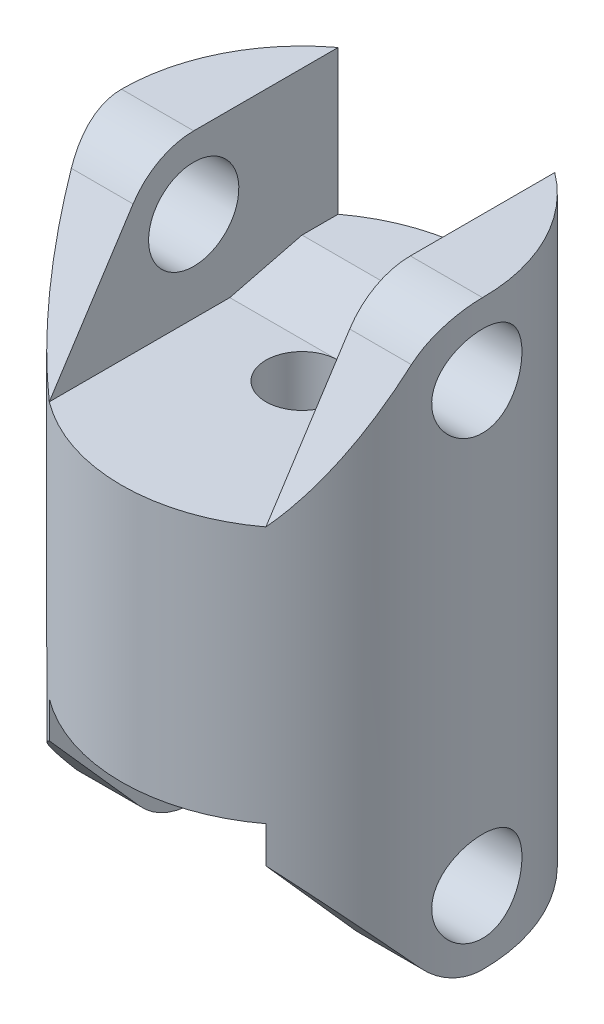
SolidWorks part; units mm, degrees
ref_plane "Front Plane" through (0, 0, 0) normal (0, 0, 1) x (1, 0, 0)
ref_plane "Top Plane" through (0, 0, 0) normal (0, 1, 0) x (1, 0, 0)
ref_plane "Right Plane" through (0, 0, 0) normal (1, 0, 0) x (0, 0, -1)
sketch "Sketch1" plane through (0, 0, 0) normal (0, 1, 0) x (1, 0, 0)
  circle A0 centre (0, 0) radius 12.7
  dimension "D1" = 25.4
extrude "Boss-Extrude1" add sketch "Sketch1" along normal blind 40.9448
sketch "Sketch2" plane through (0, 40.9448, 0) normal (0, 1, 0) x (1, 0, 0)
  line L0 (7.62, 10.16) -> (7.62, -10.16)
  line L1 (-7.62, 10.16) -> (-7.62, -10.16)
  arc A0 (-7.62, -10.16) -> (7.62, -10.16) centre (0, 0) ccw
  arc A1 (7.62, 10.16) -> (-7.62, 10.16) centre (0, 0) ccw
  dimension "D2" = 25.4
  dimension "D1" = 7.62
  dimension "D3" = 7.62
extrude "Cut-Extrude1" cut sketch "Sketch2" against normal blind 11.43
sketch "Sketch3" plane through (0, 0, 0) normal (0, -1, 0) x (1, 0, 0)
  line L1 (-7.62, 10.16) -> (-7.62, -10.16)
  line L3 (7.62, 10.16) -> (7.62, -10.16)
  arc A4 (-7.62, 10.16) -> (7.62, 10.16) centre (0, 0) cw
  arc A5 (-7.62, -10.16) -> (7.62, -10.16) centre (0, 0) ccw
  point P1 (0, 0)
  point P4 (0, 0)
  point P7 (7.6286, 10.1536)
  point P8 (7.5962, -10.1778)
  dimension "D1" = 15.24
extrude "Cut-Extrude2" cut sketch "Sketch3" against normal blind 11.43
sketch "Sketch4" plane through (-7.62, 0, 0) normal (1, 0, 0) x (0, 0, -1)
  line L0 (10.16, 40.9448) -> (-10.16, 40.9448) construction
  line L5 (-10.16, 0) -> (10.16, 0) construction
  line L6 (10.16, 40.9448) -> (-10.16, 40.9448) construction
  line L7 (0, 40.9448) -> (-10.16, 40.9448)
  line L8 (-10.16, 40.9448) -> (-10.16, 29.5148)
  line L9 (-10.16, 29.5148) -> (-4.2649, 38.6247)
  line L10 (0, 0) -> (-12.4434, 0)
  line L11 (-10.16, 0) -> (10.16, 0) construction
  line L12 (-12.4434, 11.43) -> (-12.4434, 0) construction
  line L13 (-3.7964, 1.7046) -> (-12.4434, 11.43)
  line L14 (-12.4434, 11.43) -> (-12.4434, 0)
  circle A0 centre (0, 35.8648) radius 3.175
  circle A2 centre (0, 5.08) radius 3.175
  arc A4 (0, 40.9448) -> (-4.2649, 38.6247) centre (0, 35.8648) ccw
  arc A5 (0, 0) -> (-3.7964, 1.7046) centre (0, 5.08) cw
  dimension "D1" = 6.35
  dimension "D3" = 6.35
  dimension "D2" = 5.08
  dimension "D4" = 5.08
  dimension "D5" = 0
extrude "Cut-Extrude3" cut sketch "Sketch4" against normal through all both and the other way through all
sketch "Sketch5" plane through (0, 29.5148, 0) normal (0, 1, 0) x (1, 0, 0)
  circle A0 centre (0, 0) radius 2.54
  dimension "D1" = 5.08
extrude "Cut-Extrude4" cut sketch "Sketch5" against normal through all
sketch "Sketch6" plane through (-7.62, 0, 0) normal (1, 0, 0) x (0, 0, -1)
  line L0 (2.54, 29.5148) -> (10.16, 29.5148)
  line L1 (10.16, 29.5148) -> (-10.16, 29.5148) construction
  line L2 (10.16, 29.5148) -> (10.16, 30.7848)
  line L3 (10.16, 29.5148) -> (10.16, 40.9448) construction
  line L4 (10.16, 30.7848) -> (7.62, 30.7848)
  line L5 (7.62, 30.7848) -> (2.54, 29.5148)
  point P5 (0, 29.5148)
  dimension "D1" = 2.54
  dimension "D2" = 1.27
  dimension "D3" = 2.54
extrude "Boss-Extrude2" add sketch "Sketch6" along normal up to surface (15.24 mm away) up to face at (7.62, 35.8648, -3.175)
sketch "Sketch7" plane through (0, 29.5148, 0) normal (0, 1, 0) x (1, 0, 0)
  line L0 (-7.62, 10.16) -> (7.62, 10.16)
  arc A0 (7.62, 10.16) -> (-7.62, 10.16) centre (0, 0) ccw
  arc M1 (7.62, 10.16) -> (-7.62, 10.16) centre (0, 0) ccw
  line M2 (-7.62, 10.16) -> (7.62, 10.16)
extrude "Boss-Extrude3" add sketch "Sketch7" along normal up to surface (1.27 mm away) contours M2 M1 up to face at (0, 30.7848, -8.89)
